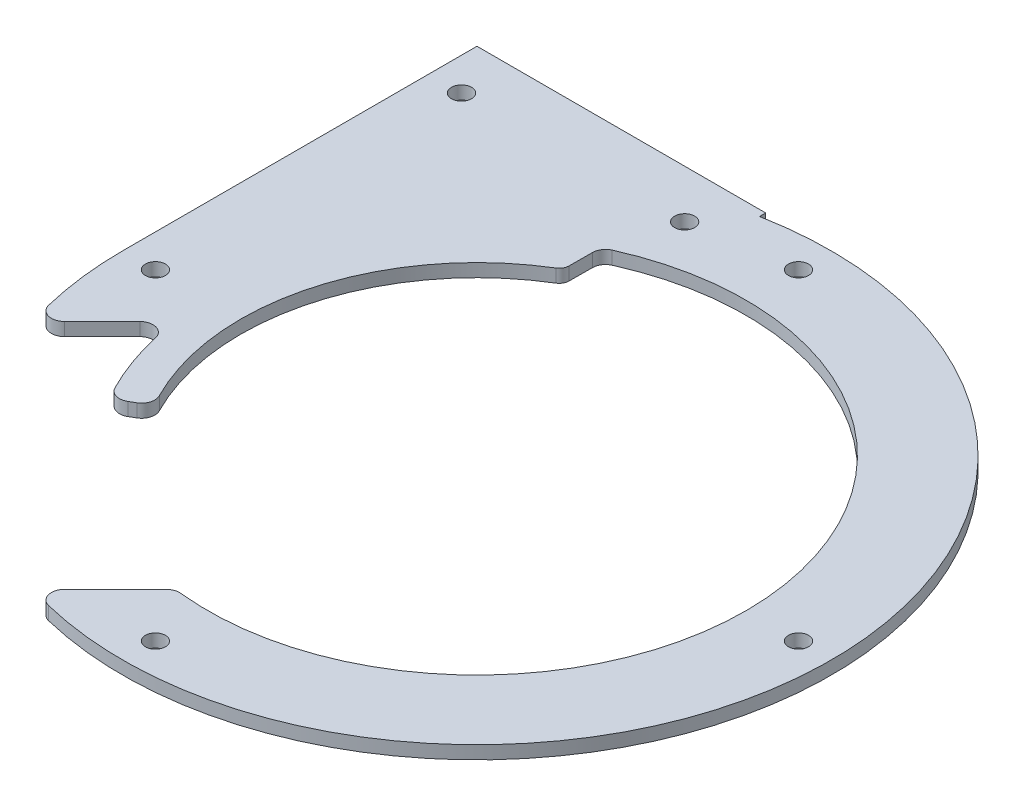
SolidWorks part; units mm, degrees
material "Thornel Mat VMA"
ref_plane "前视基准面" through (0, 0, 0) normal (0, 0, 1) x (1, 0, 0)
ref_plane "上视基准面" through (0, 0, 0) normal (0, 1, 0) x (1, 0, 0)
ref_plane "右视基准面" through (0, 0, 0) normal (1, 0, 0) x (0, 0, -1)
sketch "草图1" plane through (0, 0, 0) normal (0, 1, 0) x (1, 0, 0)
  line L0 (-54, 0) -> (-54, 54)
  line L1 (-54, 54) -> (-10, 54)
  line L2 (-10, 54) -> (-10, 53.066)
  line L3 (-32, 0) -> (-32, 54) construction
  line L4 (-15, 54) -> (-15, 46.6476) construction
  line L5 (-15, 54) -> (-15, 43.7493) construction
  line L6 (-49, 0) -> (-49, 54) construction
  line L7 (-10, 54) -> (-10, 43.7493) construction
  line L8 (-49, 46.6476) -> (-15, 46.6476) construction
  line L9 (-54, 54) -> (-54, 74) construction
  line L10 (-54, 74) -> (-10, 74) construction
  line L11 (-10, 74) -> (-10, 54) construction
  arc A0 (-54, 0) -> (-10, 53.066) centre (0, 0) ccw
  circle A1 centre (0, 0) radius 41
  circle A2 centre (0, 0) radius 32 construction
  circle A4 centre (0, 0) radius 49 construction
  circle A5 centre (-15, 46.6476) radius 1.525
  circle A6 centre (0, 49) radius 1.525
  circle A7 centre (49, 0) radius 1.525
  circle A8 centre (0, -49) radius 1.525
  circle A9 centre (-49, 0) radius 1.525
  circle A20 centre (0, 0) radius 54 construction
  circle A21 centre (-49, 46.6476) radius 1.525
  dimension "D1" = 82
  dimension "D8" = 3.05
  dimension "D4" = 17
  dimension "D2" = 9
  dimension "D3" = 8
  dimension "D5" = 5
  dimension "D6" = 20
  dimension "D7" = 4
extrude "凸台-拉伸1" add sketch "草图1" along normal blind 2
sketch "草图2" plane through (0, 0, 0) normal (0, 1, 0) x (1, 0, 0)
  line L0 (0, 0) -> (-41, 0) construction
  line L1 (-41, 0) -> (-37.47, 0)
  line L2 (0, 0) -> (-49, 0) construction
  line L3 (-18, 31.1769) -> (0, 0) construction
  line L4 (0, 0) -> (-17.9732, 36.8506) construction
  line L5 (-17.996, 32.0266) -> (-17.9732, 36.8506)
  line L6 (-35.9712, 1.44) -> (0, 0) construction
  arc A0 (-18.7161, 30.7523) -> (-35.9712, 1.44) centre (0, 0) ccw
  arc A1 (-17.9732, 36.8506) -> (-41, 0) centre (0, 0) ccw
  circle A2 centre (0, 0) radius 41 construction
  arc A6 (-35.9712, 1.44) -> (-37.47, 0) centre (-37.47, 1.5) cw
  arc A7 (-18.7161, 30.7523) -> (-17.996, 32.0266) centre (-19.496, 32.0337) ccw
  dimension "D1" = 72
  dimension "D4" = 1.5
  dimension "D5" = 1.5
  dimension "D6" = 60
  dimension "D7" = 4
extrude "凸台-拉伸3" add sketch "草图2" along normal up to surface (2 mm away) up to face at (-49, 2, 1.525)
fillet "圆角1" radius 2 2 edges at (-17.9732, 1, -36.8506) (-41, 1, 0)
sketch "草图4" plane through (0, 0, 0) normal (0, -1, 0) x (1, 0, 0)
  line L0 (-38.9487, 0) -> (-37.47, 0) construction
  line L1 (-38.9487, 0) -> (-37.47, 0)
  line L2 (0, 0) -> (-37.47, 0) construction
  line L3 (-31.1769, 18) -> (-35.507, 20.5)
  line L4 (-31.1769, 18) -> (0, 0) construction
  arc A0 (-40.9461, 2.1026) -> (-38.9487, 0) centre (-38.9487, 2) ccw construction
  arc A1 (-35.9712, -1.44) -> (-37.47, 0) centre (-37.47, -1.5) ccw construction
  arc A2 (-40.9461, 2.1026) -> (-38.9487, 0) centre (-38.9487, 2) ccw
  arc A3 (-35.9712, -1.44) -> (-37.47, 0) centre (-37.47, -1.5) ccw
  arc A4 (-31.1769, 18) -> (-35.9712, -1.44) centre (0, 0) ccw
  arc A5 (-16.7987, -37.4006) -> (-40.9461, 2.1026) centre (0, 0) ccw construction
  arc A6 (-35.507, 20.5) -> (-40.9461, 2.1026) centre (0, 0) ccw
  dimension "D1" = 30
extrude "凸台-拉伸5" add sketch "草图4" against normal blind 2
sketch "草图5" plane through (0, 0, 0) normal (0, -1, 0) x (1, 0, 0)
  line L0 (0, 0) -> (-38.1838, 38.1838) construction
  line L1 (0, 0) -> (-36, 0) construction
  line L2 (0, 0) -> (-51.5229, 16.1676) construction
  line L3 (0, 0) -> (-16.1676, 51.5229) construction
  line L6 (-16.1676, 51.5229) -> (-5.3006, 40.6559)
  line L7 (-51.5229, 16.1676) -> (-40.6559, 5.3006)
  arc A0 (-31.1769, 18) -> (-18.7161, -30.7523) centre (0, 0) ccw construction
  arc A1 (-10, -53.066) -> (-54, 0) centre (0, 0) ccw construction
  arc A2 (-51.5229, 16.1676) -> (-16.1676, 51.5229) centre (0, 0) cw
  arc A5 (-16.7987, -37.4006) -> (-35.507, 20.5) centre (0, 0) ccw construction
  arc A6 (-40.6559, 5.3006) -> (-5.3006, 40.6559) centre (0, 0) cw
  dimension "D1" = 45
  dimension "D2" = 50
extrude "切除-拉伸1" cut sketch "草图5" against normal blind 10
fillet "圆角3" radius 2 6 edges at (-31.1769, 1, 18) (-5.3006, 1, 40.6559) (-35.507, 1, 20.5) (-40.6559, 1, 5.3006) (-51.5229, 1, 16.1676) (-16.1676, 1, 51.5229)
